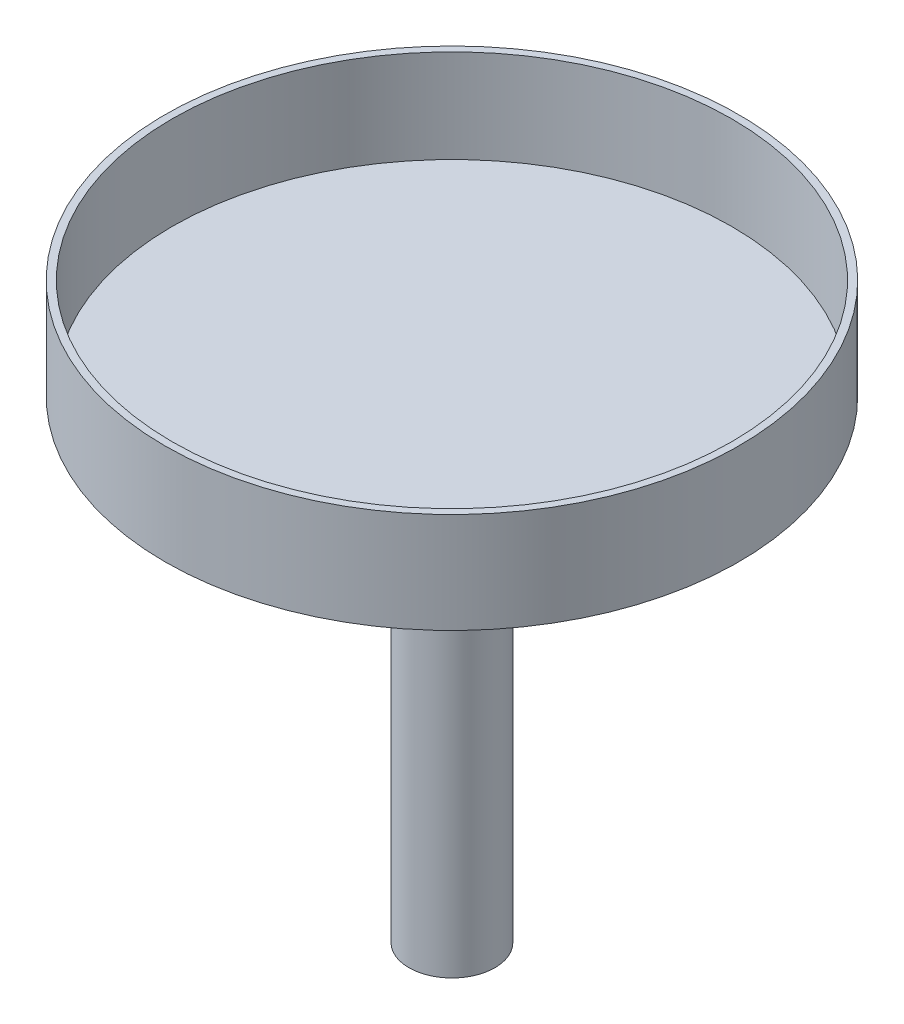
SolidWorks part; units mm, degrees
ref_plane "Front Plane" through (0, 0, 0) normal (0, 0, 1) x (1, 0, 0)
ref_plane "Top Plane" through (0, 0, 0) normal (0, 1, 0) x (1, 0, 0)
ref_plane "Right Plane" through (0, 0, 0) normal (1, 0, 0) x (0, 0, -1)
sketch "Sketch2" plane through (0, 0, 0) normal (0, 0, 1) x (1, 0, 0)
  line L0 (0, 34.7727) -> (0, -53.7121) construction
  line L1 (30, -330) -> (30, 0)
  line L2 (30, 0) -> (200, 0)
  line L3 (200, 0) -> (200, 70)
  line L4 (200, 70) -> (195, 70)
  line L5 (195, 70) -> (195, 5)
  line L6 (195, 5) -> (0, 5)
  line L7 (0, 5) -> (0, -330)
  line L8 (0, -330) -> (30, -330)
  dimension "D1" = 5
  dimension "D2" = 5
  dimension "D3" = 30
  dimension "D4" = 70
  dimension "D5" = 200
  dimension "D6" = 400
revolve "Revolve1" add sketch "Sketch2" angle 360 about L0
